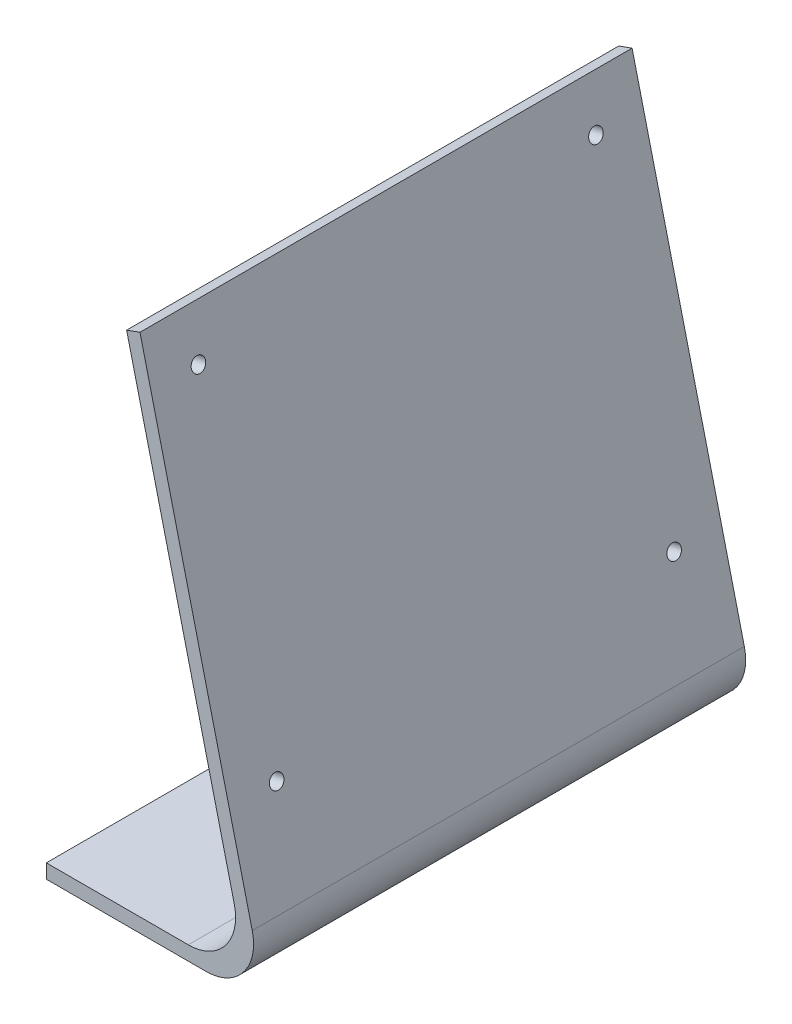
SolidWorks part; units mm, degrees
ref_plane "Front Plane" through (0, 0, 0) normal (0, 0, 1) x (1, 0, 0)
ref_plane "Top Plane" through (0, 0, 0) normal (0, 1, 0) x (1, 0, 0)
ref_plane "Right Plane" through (0, 0, 0) normal (1, 0, 0) x (0, 0, -1)
sketch "Sketch1" plane through (0, 0, 0) normal (0, 0, 1) x (1, 0, 0)
  line L0 (-50.53, 0) -> (-50.53, 3)
  line L1 (-50.53, 3) -> (-20.53, 3)
  line L2 (-50.53, 0) -> (-16.7319, 0)
  line L3 (-7.0146, 12.361) -> (-30.7379, 110)
  line L4 (-30.7379, 110) -> (-33.5595, 108.9811)
  line L5 (-33.5595, 108.9811) -> (-10.8127, 15.361)
  arc A0 (-10.8127, 15.361) -> (-20.53, 3) centre (-20.53, 13) cw
  arc A1 (-16.7319, 0) -> (-7.0146, 12.361) centre (-16.7319, 10) ccw
  dimension "D1" = 10
  dimension "D2" = 3
  dimension "D3" = 30
  dimension "D4" = 110
extrude "Boss-Extrude1" add sketch "Sketch1" along normal mid plane 104
sketch "Эскиз1" plane through (-3.7876, -0.9203, 0) normal (0.9717, 0.2361, 0) x (0, 0, -1)
  line L0 (-52, 114.1474) -> (52, 114.1474) construction
  line L1 (-47, 109.1474) -> (47, 109.1474) construction
  line L2 (-47, 109.1474) -> (-47, 29.1474) construction
  line L3 (-47, 29.1474) -> (47, 29.1474) construction
  line L4 (47, 109.1474) -> (47, 29.1474) construction
  line L5 (-47, 109.1474) -> (47, 29.1474) construction
  line L6 (-47, 29.1474) -> (47, 109.1474) construction
  line L7 (-52, 13.6677) -> (-52, 114.1474) construction
  point P0 (0, 69.1474)
  dimension "D1" = 80
  dimension "D2" = 94
  dimension "D3" = 5
  dimension "D4" = 5
sketch "Эскиз2" plane through (-3.7876, -0.9203, 0) normal (0.9717, 0.2361, 0) x (0, 0, -1)
  line L0 (-47, 109.1474) -> (-47, 29.1474) construction
  line L1 (-47, 109.1474) -> (47, 109.1474) construction
  line L2 (0, 69.1474) -> (0, 79.7671) construction
  line L3 (-47, 109.1474) -> (47, 29.1474) construction
  line L4 (0, 69.1474) -> (-10.9608, 69.1474) construction
  circle A0 centre (-42, 104.1474) radius 1.5
  circle A1 centre (42, 104.1474) radius 1.5
  circle A2 centre (42, 34.1474) radius 1.5
  circle A3 centre (-42, 34.1474) radius 1.5
  dimension "D1" = 5
  dimension "D2" = 5
extrude "Вырез-Вытянуть1" cut sketch "Эскиз2" against normal up to next
